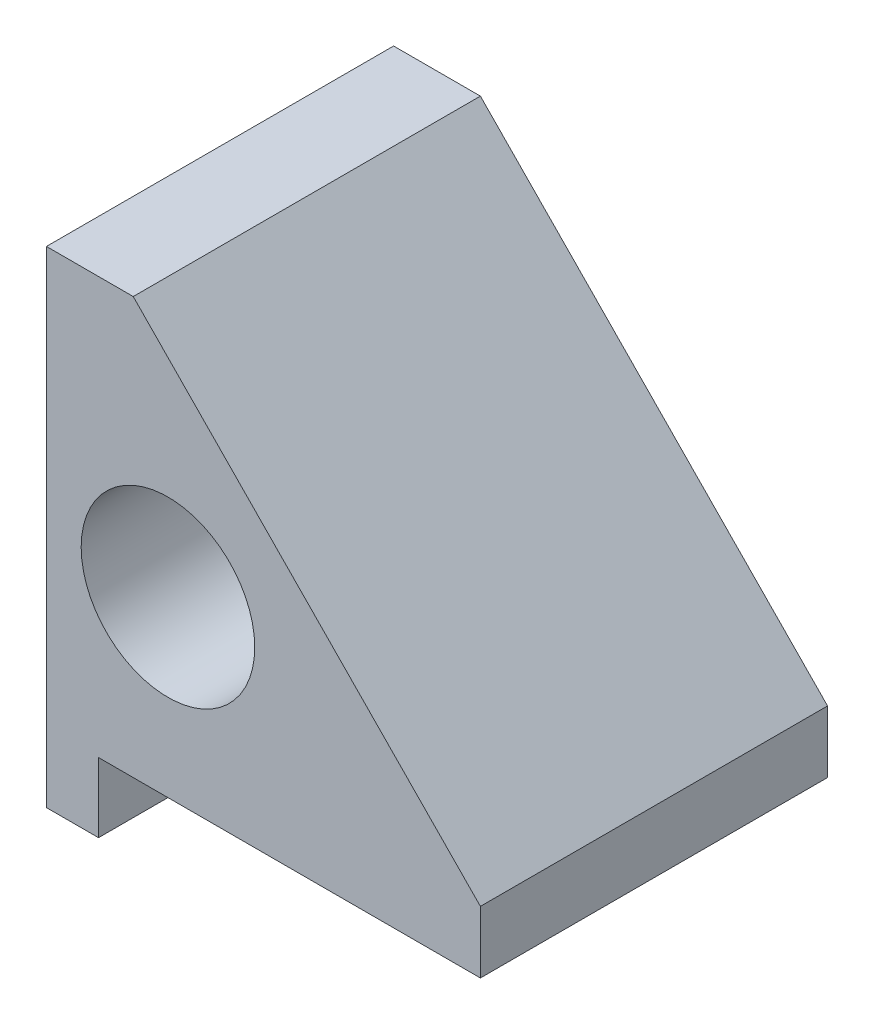
SolidWorks part; units mm, degrees
ref_plane "Plan1" through (0, 0, 0) normal (0, 0, 1) x (1, 0, 0)
ref_plane "Plan2" through (0, 0, 0) normal (0, 1, 0) x (1, 0, 0)
ref_plane "Plan3" through (0, 0, 0) normal (1, 0, 0) x (0, 0, -1)
sketch "Esquisse1" plane through (0, 0, 0) normal (0, 0, 1) x (1, 0, 0)
  line L0 (0, 0) -> (22, 0)
  line L1 (22, 0) -> (22, 3.5745)
  line L2 (22, 3.5745) -> (2, 24)
  line L3 (2, 24) -> (-3, 24)
  line L4 (-3, 24) -> (-3, -4)
  line L5 (-3, -4) -> (0, -4)
  line L6 (0, -4) -> (0, 0)
  circle A0 centre (4, 10) radius 5
  dimension "D7" = 10
  dimension "D1" = 45.603
  dimension "D2" = 5
  dimension "D3" = 25
  dimension "D4" = 4
  dimension "D5" = 22
  dimension "D6" = 28
  dimension "D8" = 14
  dimension "D9" = 7
extrude "Base-Extrusion" add sketch "Esquisse1" along normal blind 20
